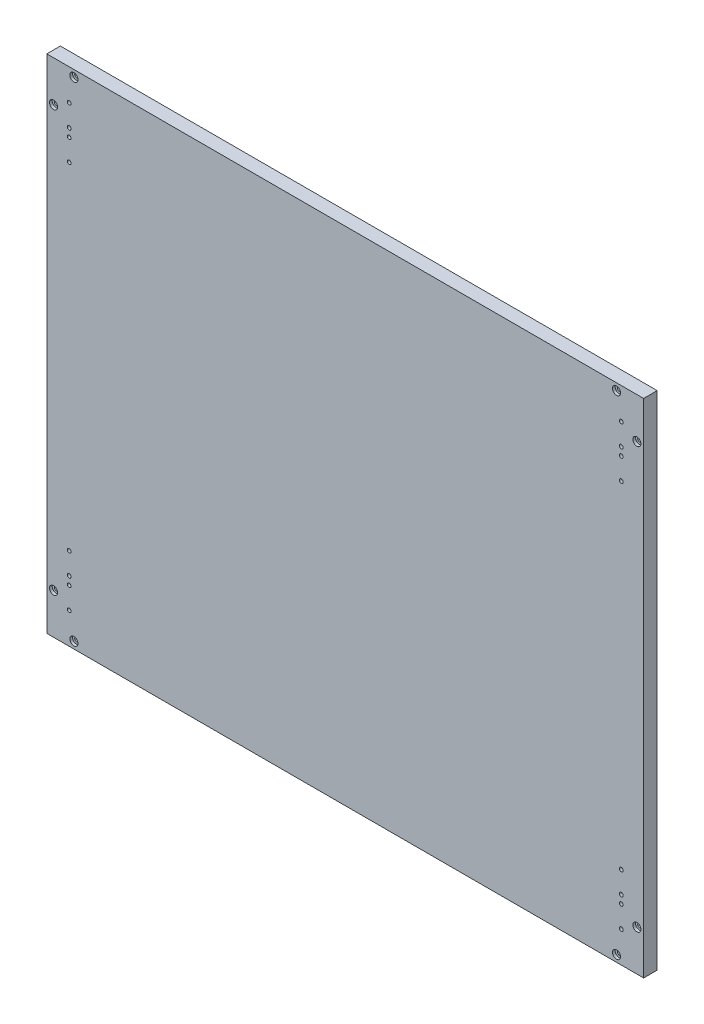
SolidWorks part; units mm, degrees
ref_plane "Front Plane" through (0, 0, 0) normal (0, 0, 1) x (1, 0, 0)
ref_plane "Top Plane" through (0, 0, 0) normal (0, 1, 0) x (1, 0, 0)
ref_plane "Right Plane" through (0, 0, 0) normal (1, 0, 0) x (0, 0, -1)
sketch "Sketch1" plane through (0, 0, 0) normal (0, 0, 1) x (1, 0, 0)
  line L1 (0, 0) -> (420, 0)
  line L2 (0, 0) -> (0, 350)
  line L3 (0, 350) -> (420, 350)
  line L4 (420, 0) -> (420, 350)
  dimension "D1" = 350
  dimension "D2" = 420
extrude "Boss-Extrude1" add sketch "Sketch1" along normal blind 10
sketch "Sketch29" plane through (0, 0, 0) normal (0, 0, -1) x (-1, 0, 0)
  line L0 (-420, 0) -> (-420, 350) construction
  line L1 (10, -10) -> (-430, -10)
  line L2 (10, -10) -> (10, 360)
  line L3 (10, 360) -> (-430, 360)
  line L4 (-430, -10) -> (-430, 360)
  line L5 (-420, 350) -> (0, 350) construction
  line L6 (0, 350) -> (0, 0) construction
  line L7 (0, 0) -> (-420, 0) construction
  dimension "D1" = 10
  dimension "D2" = 10
  dimension "D3" = 10
  dimension "D4" = 10
extrude "Boss-Extrude11" add sketch "Sketch29" against normal blind 10
sketch "Sketch30" plane through (0, 0, 0) normal (0, 0, -1) x (-1, 0, 0)
  line L0 (10, 360) -> (-430, 360) construction
  line L1 (-430, 360) -> (-430, -10) construction
  line L2 (10, -10) -> (10, 360) construction
  line L3 (-430, -10) -> (10, -10) construction
  circle A0 centre (-424, 354) radius 3
  circle A1 centre (-424, -4) radius 3
  circle A2 centre (4, -4) radius 3
  circle A3 centre (4, 354) radius 3
  dimension "D1" = 6
  dimension "D2" = 6
  dimension "D3" = 6
  dimension "D4" = 6
  dimension "D5" = 6
  dimension "D6" = 6
  dimension "D7" = 6
  dimension "D8" = 6
  dimension "D9" = 6
extrude "Cut-Extrude1" cut sketch "Sketch30" against normal through all
sketch "Sketch32" plane through (0, 0, 10) normal (0, 0, 1) x (1, 0, 0)
  line L0 (430, 360) -> (430, -10) construction
  line L1 (409, 340) -> (418, 340)
  line L2 (409, 340) -> (409, 296)
  line L3 (409, 296) -> (418, 296)
  line L4 (418, 340) -> (418, 296)
  line L5 (-10, 360) -> (430, 360) construction
  line L6 (430, 175) -> (-10, 175)
  line L7 (-10, -10) -> (-10, 360) construction
  line L8 (210, -10) -> (210, 360)
  line L9 (430, -10) -> (-10, -10) construction
  line L10 (409, 10) -> (409, 54)
  line L11 (409, 10) -> (418, 10)
  line L12 (409, 54) -> (418, 54)
  line L13 (418, 10) -> (418, 54)
  line L14 (11, 10) -> (11, 54)
  line L15 (11, 54) -> (2, 54)
  line L16 (2, 10) -> (2, 54)
  line L17 (11, 296) -> (2, 296)
  line L18 (11, 340) -> (11, 296)
  line L19 (11, 340) -> (2, 340)
  line L20 (2, 340) -> (2, 296)
  circle A0 centre (413.5, 337) radius 1.4
  circle A1 centre (413.5, 321) radius 1.4
  circle A2 centre (413.5, 315) radius 1.4
  circle A3 centre (413.5, 299) radius 1.4
  circle A4 centre (413.5, 51) radius 1.4
  circle A5 centre (413.5, 35) radius 1.4
  circle A6 centre (413.5, 29) radius 1.4
  circle A7 centre (413.5, 13) radius 1.4
  circle A8 centre (6.5, 51) radius 1.4
  circle A9 centre (6.5, 13) radius 1.4
  circle A10 centre (6.5, 29) radius 1.4
  circle A11 centre (6.5, 35) radius 1.4
  circle A12 centre (6.5, 299) radius 1.4
  circle A13 centre (6.5, 315) radius 1.4
  circle A14 centre (6.5, 321) radius 1.4
  circle A15 centre (6.5, 337) radius 1.4
  dimension "D5" = 2.8
  dimension "D1" = 12
  dimension "D2" = 9
  dimension "D3" = 20
  dimension "D4" = 44
  dimension "D6" = 3
  dimension "D7" = 16
  dimension "D8" = 6
  dimension "D9" = 16
  dimension "D10" = 4.5
  dimension "D11" = 4.5
  dimension "D12" = 4.5
  dimension "D13" = 4.5
sketch "Sketch33" plane through (0, 0, 10) normal (0, 0, 1) x (1, 0, 0)
  circle A0 centre (-4, 354) radius 3.4694
  circle A1 centre (-4, -4) radius 4.503
  circle A2 centre (424, -4) radius 4.2826
  circle A3 centre (424, 354) radius 4.6276
extrude "Boss-Extrude12" add sketch "Sketch33" against normal blind 10
extrude "Cut-Extrude3" cut sketch "Sketch32" against normal blind 10 contours A15 | A14 | A13 | A12 | A8 | A11 | A10 | A9 | A7 | A6 | A5 | A4 | A3 | A1 | A2 | A0
sketch "Sketch35" plane through (0, 0, 0) normal (0, 0, -1) x (-1, 0, 0)
  line L0 (10, 360) -> (-430, 360) construction
  line L1 (-430, 360) -> (-430, -10) construction
  line L2 (10, -10) -> (10, 360) construction
  line L3 (-430, -10) -> (10, -10) construction
  circle A0 centre (-410, 355) radius 1.4
  circle A1 centre (-10, 355) radius 1.4
  circle A2 centre (5, 330) radius 1.4
  circle A3 centre (5, 20) radius 1.4
  circle A4 centre (-10, -5) radius 1.4
  circle A5 centre (-410, -5) radius 1.4
  circle A6 centre (-425, 330) radius 1.4
  circle A7 centre (-425, 20) radius 1.4
  dimension "D1" = 2.8
  dimension "D2" = 5
  dimension "D3" = 20
  dimension "D4" = 5
  dimension "D5" = 20
  dimension "D6" = 5
  dimension "D7" = 5
  dimension "D8" = 20
  dimension "D9" = 20
  dimension "D10" = 5
  dimension "D11" = 5
  dimension "D12" = 30
  dimension "D13" = 5
  dimension "D14" = 30
  dimension "D15" = 30
  dimension "D16" = 5
  dimension "D17" = 30
extrude "Cut-Extrude5" cut sketch "Sketch35" against normal blind 10
sketch "Sketch37" plane through (0, 0, 10) normal (0, 0, 1) x (1, 0, 0)
  circle A0 centre (10, 355) radius 3
  circle A1 centre (-5, 330) radius 3
  circle A2 centre (-5, 20) radius 3
  circle A3 centre (10, -5) radius 3
  circle A4 centre (410, -5) radius 3
  circle A5 centre (425, 20) radius 3
  circle A6 centre (410, 355) radius 3
  circle A7 centre (425, 330) radius 3
  dimension "D1" = 6
extrude "Cut-Extrude7" cut sketch "Sketch37" against normal blind 2
